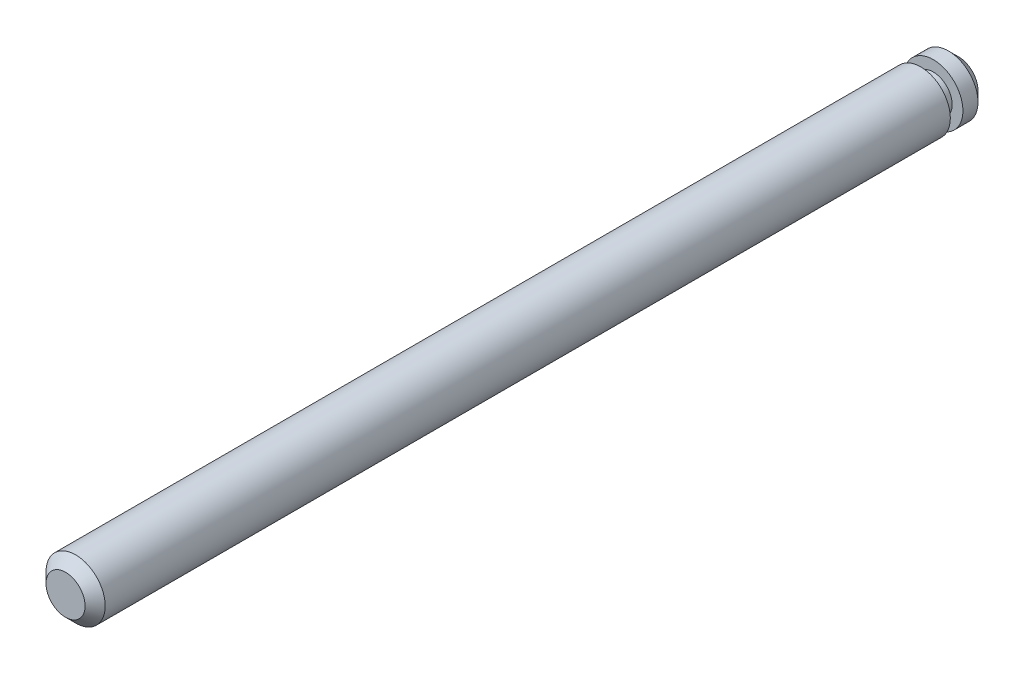
SolidWorks part; units mm, degrees
ref_plane "Front Plane" through (0, 0, 0) normal (0, 0, 1) x (1, 0, 0)
ref_plane "Top Plane" through (0, 0, 0) normal (0, 1, 0) x (1, 0, 0)
ref_plane "Right Plane" through (0, 0, 0) normal (1, 0, 0) x (0, 0, -1)
sketch "Sketch1" plane through (0, 0, 0) normal (0, 0, 1) x (1, 0, 0)
  circle A0 centre (0, 0) radius 1.4948
  dimension "D1" = 2.9896
extrude "Extrude1" add sketch "Sketch1" along normal blind 43.18
sketch "Sketch2" plane through (0, 0, 0) normal (0, 0, -1) x (-1, 0, 0)
  circle A0 centre (0, 0) radius 0.9525
  dimension "D1" = 1.905
extrude "Extrude2" add sketch "Sketch2" along normal blind 0.635
sketch "Sketch3" plane through (0, 0, -0.635) normal (0, 0, -1) x (-1, 0, 0)
  circle A0 centre (0, 0) radius 1.4948
extrude "Extrude3" add sketch "Sketch3" along normal blind 1.27
chamfer "Chamfer1" distance 0.508 angle 45 2 edges at (-1.4948, 0, -1.905) (1.4948, 0, 43.18)
